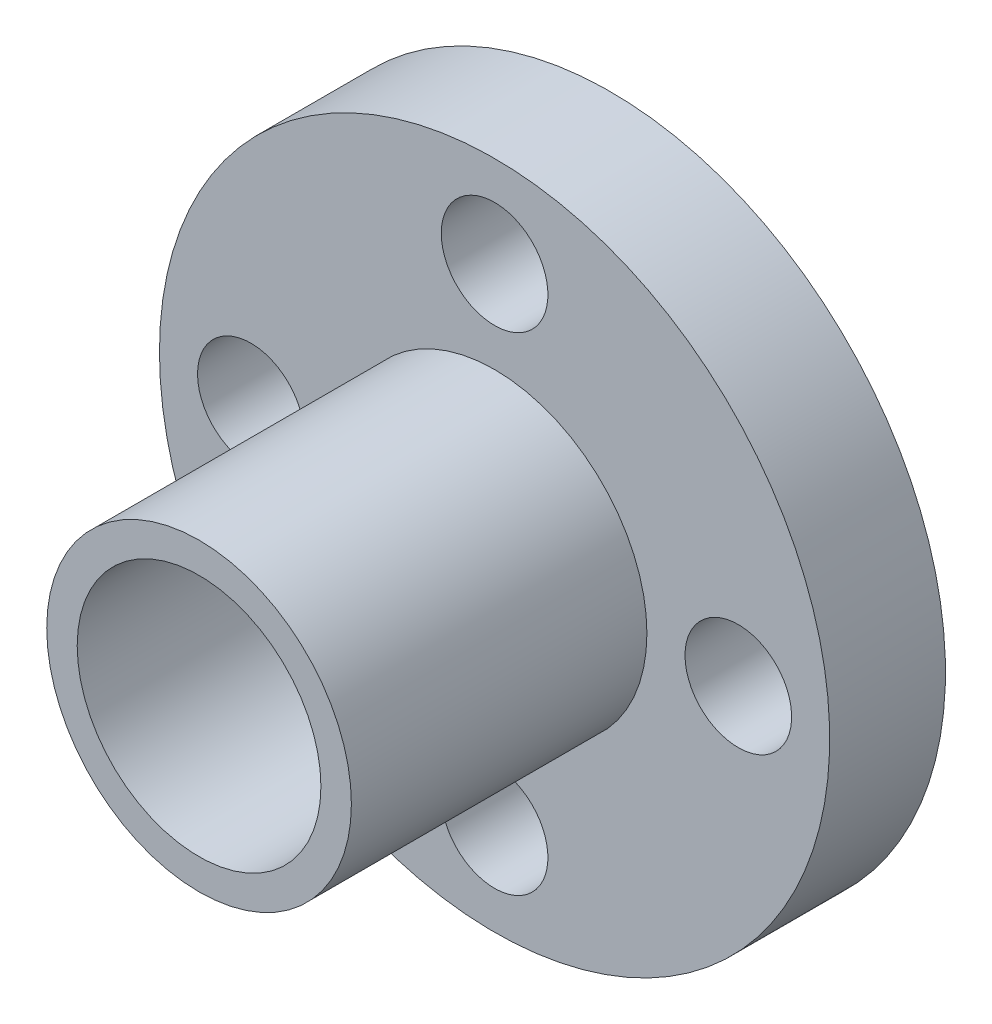
SolidWorks part; units mm, degrees
ref_plane "前视基准面" through (0, 0, 0) normal (0, 0, 1) x (1, 0, 0)
ref_plane "上视基准面" through (0, 0, 0) normal (0, 1, 0) x (1, 0, 0)
ref_plane "右视基准面" through (0, 0, 0) normal (1, 0, 0) x (0, 0, -1)
sketch "草图1" plane through (0, 0, 0) normal (0, 0, 1) x (1, 0, 0)
  circle A0 centre (0, 0) radius 11
  circle A1 centre (0, 0) radius 5
  circle A2 centre (0, 0) radius 8 construction
  circle A3 centre (-8, 0) radius 1.75
  circle A4 centre (0, 8) radius 1.75
  circle A5 centre (8, 0) radius 1.75
  circle A6 centre (0, -8) radius 1.75
  point P16 (0, 0)
  dimension "D1" = 22
  dimension "D2" = 10
  dimension "D3" = 16
  dimension "D4" = 3.5
  dimension "D5" = 4
extrude "凸台-拉伸1" add sketch "草图1" along normal blind 3.8
sketch "草图2" plane through (0, 0, 0) normal (0, 0, -1) x (-1, 0, 0)
  circle A0 centre (0, 0) radius 4
  circle A1 centre (0, 0) radius 5 construction
  circle A2 centre (0, 0) radius 5
  dimension "D1" = 8
extrude "凸台-拉伸2" add sketch "草图2" against normal blind 15 from offset 1.5
